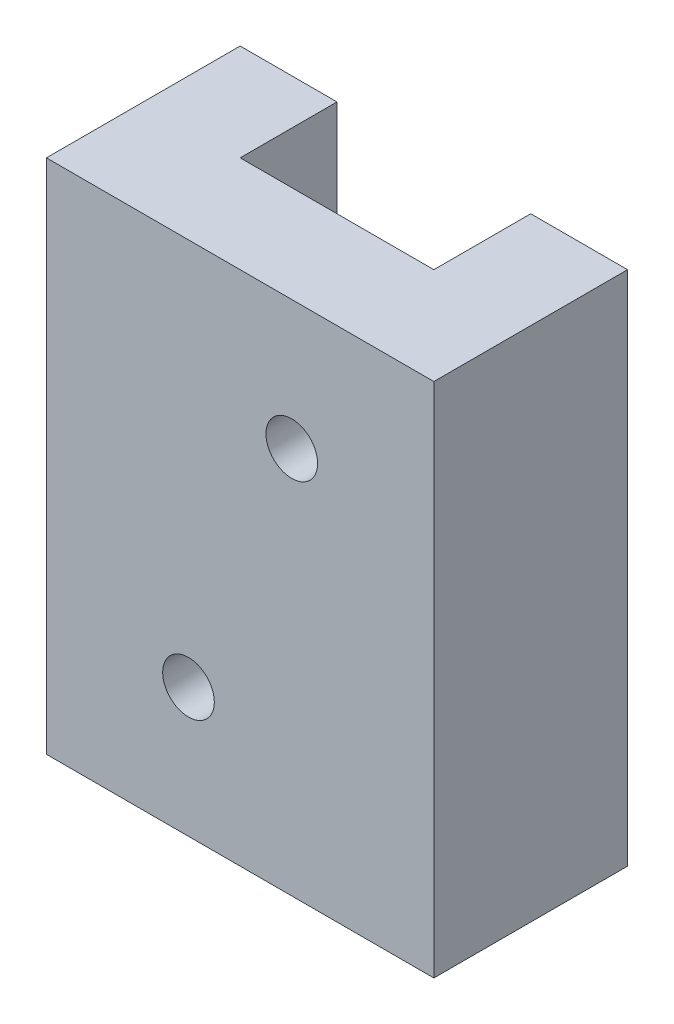
SolidWorks part; units mm, degrees
ref_plane "Plan de face" through (0, 0, 0) normal (0, 0, 1) x (1, 0, 0)
ref_plane "Plan de dessus" through (0, 0, 0) normal (0, 1, 0) x (1, 0, 0)
ref_plane "Plan de droite" through (0, 0, 0) normal (1, 0, 0) x (0, 0, -1)
sketch "Esquisse1" plane through (0, 0, 0) normal (0, 1, 0) x (1, 0, 0)
  line L0 (-3.75, 0) -> (-7.5, 0)
  line L1 (-3.75, -3.75) -> (3.75, -3.75)
  line L5 (-3.75, -3.75) -> (-3.75, 0)
  line L6 (3.75, -3.75) -> (3.75, 0)
  line L7 (-7.5, -7.5) -> (7.5, -7.5)
  line L11 (3.75, 0) -> (7.5, 0)
  line L12 (-7.5, 0) -> (-7.5, -7.5)
  line L13 (7.5, 0) -> (7.5, -7.5)
  point P0 (0, 0)
  point P6 (0, 0)
extrude "Boss.-Extru.2" add sketch "Esquisse1" along normal blind 20
sketch "Esquisse3" plane through (0, 0, 7.5) normal (0, 0, 1) x (1, 0, 0)
  circle A4 centre (2, 15) radius 1
  circle A5 centre (-2, 5) radius 1
extrude "Enlèv. mat.-Extru.2" cut sketch "Esquisse3" against normal up to surface (3.75 mm away) up to face at (0, 10, 3.75)
